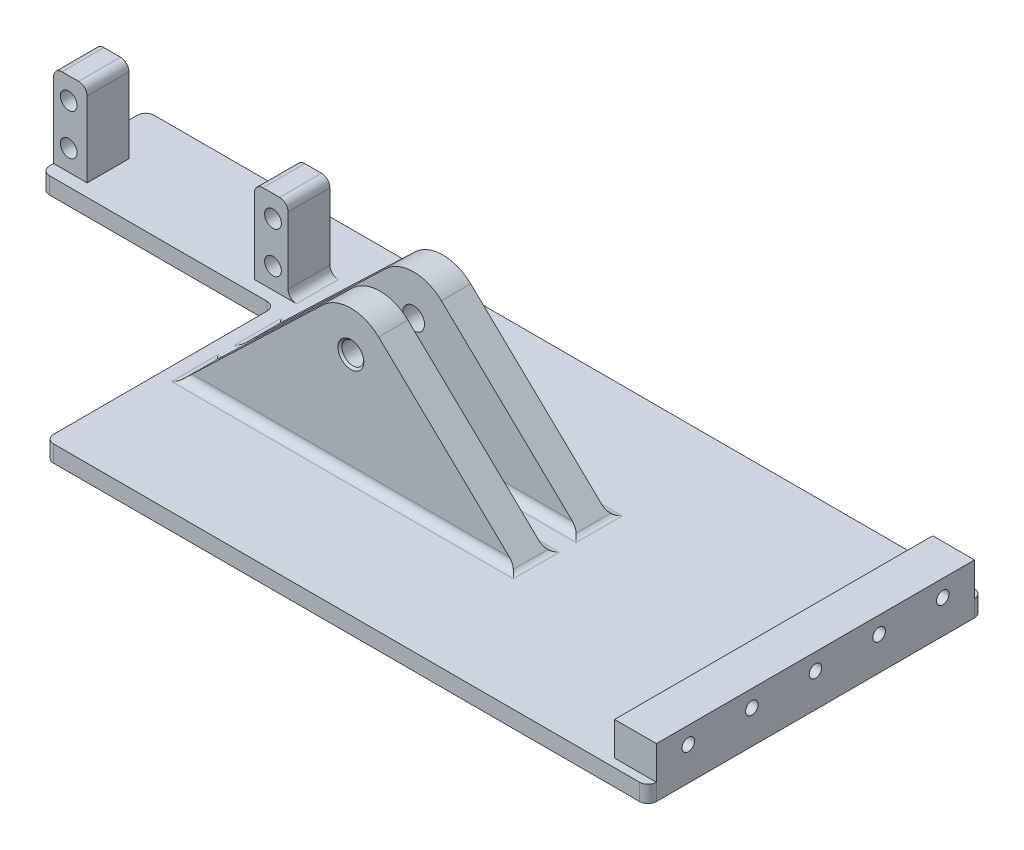
SolidWorks part; units mm, degrees
ref_plane "Front Plane" through (0, 0, 0) normal (0, 0, 1) x (1, 0, 0)
ref_plane "Top Plane" through (0, 0, 0) normal (0, 1, 0) x (1, 0, 0)
ref_plane "Right Plane" through (0, 0, 0) normal (1, 0, 0) x (0, 0, -1)
sketch "Sketch1" plane through (0, 0, 0) normal (0, 0, 1) x (1, 0, 0)
  line L0 (-6.6383, 6.9349) -> (-40, -25)
  line L1 (-40, -25) -> (40, -25)
  line L2 (40, -25) -> (6.6383, 6.9349)
  circle A0 centre (0, 0) radius 2.6
  arc A1 (6.6383, 6.9349) -> (-6.6383, 6.9349) centre (0, 0) ccw
  point P6 (0, -25)
  dimension "D1" = 5.2
  dimension "D2" = 7
  dimension "D3" = 80
  dimension "D4" = 25
extrude "Boss-Extrude1" add sketch "Sketch1" along normal blind 22
sketch "Sketch2" plane through (0, -25, 0) normal (0, -1, 0) x (-1, 0, 0)
  line L0 (-40, -22) -> (-40, 0) construction
  line L1 (-100, -51) -> (100, -51)
  line L2 (-100, -51) -> (-100, 29)
  line L3 (-100, 29) -> (100, 29)
  line L4 (100, -51) -> (100, 29)
  point P6 (-40, -11)
  point P7 (-100, -11)
  point P9 (0, 29)
  dimension "D1" = 200
  dimension "D2" = 80
extrude "Boss-Extrude2" add sketch "Sketch2" along normal blind 4
sketch "Sketch3" plane through (100, 0, 0) normal (1, 0, 0) x (0, 0, -1)
  line L0 (29, -25) -> (-51, -25) construction
  line L1 (-15, -25) -> (-7, -25)
  line L2 (-15, -25) -> (-15, 10)
  line L3 (-15, 10) -> (-7, 10)
  line L4 (-7, -25) -> (-7, 10)
  line L5 (0, -25) -> (0, 6.9349) construction
  dimension "D1" = 8
  dimension "D2" = 7
  dimension "D3" = 35
extrude "Cut-Extrude1" cut sketch "Sketch3" against normal through all
chamfer "Chamfer1" distance 0.5 angle 45 2 edges at (2.6, 0, 22) (2.6, 0, 0)
sketch "Sketch4" plane through (0, 0, -29) normal (0, 0, -1) x (-1, 0, 0)
  line L0 (72, -25) -> (72, 2.2972) construction
  line L1 (100, -25) -> (92, -25)
  line L2 (100, -25) -> (100, -5)
  line L3 (100, -5) -> (92, -5)
  line L4 (92, -25) -> (92, -5)
  line L5 (100, -25) -> (-100, -25) construction
  line L6 (44, -25) -> (52, -25)
  line L7 (52, -25) -> (52, -5)
  line L8 (44, -5) -> (52, -5)
  line L9 (44, -25) -> (44, -5)
  circle A0 centre (96.4, -20) radius 2
  circle A1 centre (96.4, -10.2) radius 2
  circle A2 centre (47.6, -20) radius 2
  circle A3 centre (47.6, -10.2) radius 2
  dimension "D4" = 4
  dimension "D5" = 5
  dimension "D1" = 8
  dimension "D2" = 20
  dimension "D3" = 9.8
  dimension "D6" = 4.4
  dimension "D7" = 20
extrude "Boss-Extrude3" add sketch "Sketch4" along normal blind 10 from offset 22 offset against normal yes
sketch "Sketch5" plane through (0, -25, 0) normal (0, 1, 0) x (1, 0, 0)
  line L0 (-44, 17) -> (-44, 7) construction
  line L1 (-100, -51) -> (-44, -51)
  line L2 (-100, -51) -> (-100, 4)
  line L3 (-100, 4) -> (-44, 4)
  line L4 (-44, -51) -> (-44, 4)
  dimension "D1" = 55
extrude "Cut-Extrude2" cut sketch "Sketch5" against normal blind 7
fillet "Fillet1" radius 2 19 edges at (-100, -5, -12) (-92, -5, -12) (-44, -5, -12) (-52, -5, -12) (-44, -25, -12) (0, -25, 0) (0, -25, 15) (-40, -25, 18.5) (0, -25, 7) (-40, -25, 3.5) (0, -25, 22) (40, -25, 3.5) (40, -25, 18.5) (100, -27, -29) (100, -27, 51) (-100, -27, -29) (-44, -27, -4) (-44, -27, 51) (-100, -27, -4)
sketch "Sketch7" plane through (100, 0, 0) normal (1, 0, 0) x (0, 0, -1)
  line L1 (-49, -25) -> (27, -25)
  line L2 (-49, -25) -> (-49, -17)
  line L3 (-49, -17) -> (27, -17)
  line L4 (27, -25) -> (27, -17)
  circle A0 centre (-41.4, -21) radius 1.5
  circle A1 centre (-26.2, -21) radius 1.5
  circle A2 centre (-11, -21) radius 1.5
  circle A3 centre (4.2, -21) radius 1.5
  circle A4 centre (19.4, -21) radius 1.5
  point P7 (-49, -21)
  point P8 (-26.2642, -21)
  dimension "D2" = 3
  dimension "D1" = 8
  dimension "D3" = 76
  dimension "D4" = 7.6
  dimension "D6" = 15.2
  dimension "D5" = 5
extrude "Boss-Extrude4" add sketch "Sketch7" against normal blind 10
